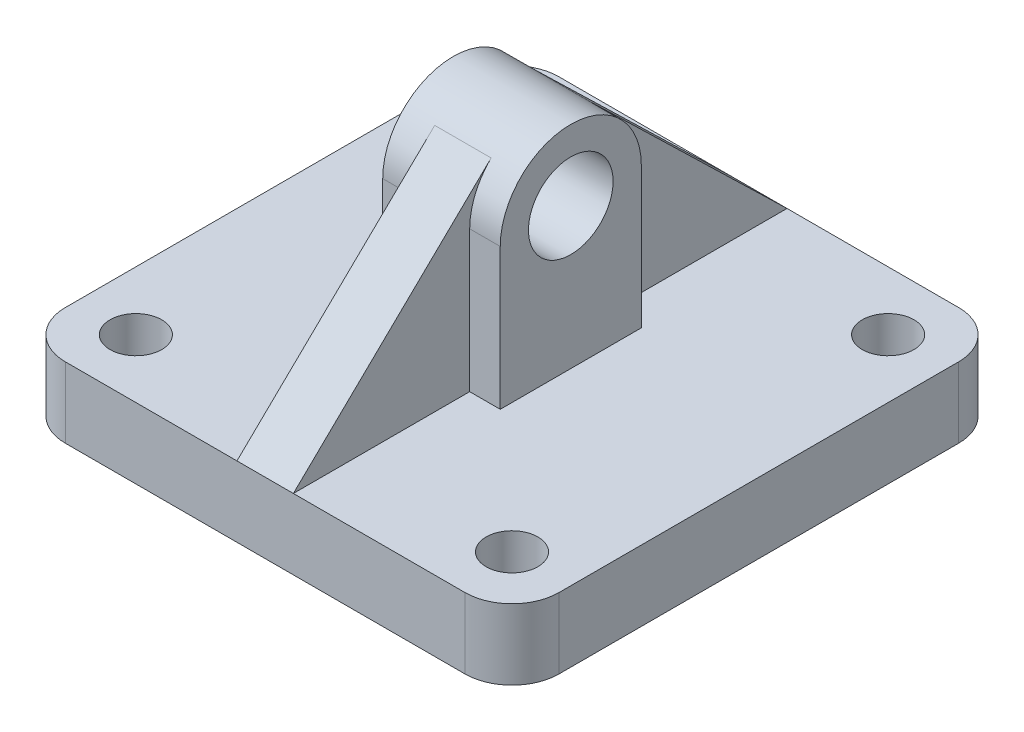
SolidWorks part; units mm, degrees
material "1060 Сплав"
ref_plane "Спереди" through (0, 0, 0) normal (0, 0, 1) x (1, 0, 0)
ref_plane "Сверху" through (0, 0, 0) normal (0, 1, 0) x (1, 0, 0)
ref_plane "Справа" through (0, 0, 0) normal (1, 0, 0) x (0, 0, -1)
sketch "Эскиз1" plane through (0, 0, 0) normal (0, 1, 0) x (1, 0, 0)
  line L1 (42.5, -52.5) -> (-42.5, -52.5)
  line L2 (52.5, -42.5) -> (52.5, 42.5)
  line L3 (42.5, 52.5) -> (-42.5, 52.5)
  line L4 (-52.5, -42.5) -> (-52.5, 42.5)
  line L5 (52.5, -52.5) -> (-52.5, 52.5) construction
  line L6 (52.5, 52.5) -> (-52.5, -52.5) construction
  arc A0 (-42.5, -52.5) -> (-52.5, -42.5) centre (-42.5, -42.5) cw
  arc A1 (42.5, -52.5) -> (52.5, -42.5) centre (42.5, -42.5) ccw
  arc A2 (52.5, 42.5) -> (42.5, 52.5) centre (42.5, 42.5) ccw
  arc A3 (-42.5, 52.5) -> (-52.5, 42.5) centre (-42.5, 42.5) ccw
  circle A4 centre (-40, -40) radius 5.5
  circle A5 centre (-40, 40) radius 5.5
  circle A6 centre (40, 40) radius 5.5
  circle A7 centre (40, -40) radius 5.5
  point P0 (0, 0)
  point P29 (0, 0)
  dimension "D2" = 10
  dimension "D3" = 11
  dimension "D1" = 105
  dimension "D4" = 40
  dimension "D5" = 4
extrude "Бобышка-Вытянуть1" add sketch "Эскиз1" along normal blind 15
sketch "Эскиз2" plane through (0, 0, 0) normal (0, -1, 0) x (1, 0, 0)
  circle A0 centre (0, 0) radius 35
  dimension "D1" = 70
extrude "Вырез-Вытянуть1" cut sketch "Эскиз2" against normal blind 10
sketch "Эскиз3" plane through (0, 0, -52.5) normal (0, 0, 1) x (1, 0, 0)
  line L0 (-42.5, 0) -> (42.5, 0) construction
  line L1 (0, -1000) -> (0, 49000) construction
  circle A0 centre (0, -5) radius 10
  point P2 (0, 0)
  dimension "D1" = 20
  dimension "D2" = 5
extrude "Вырез-Вытянуть2" cut sketch "Эскиз3" against normal up to surface (18.959 mm away)
sketch "Эскиз5" plane through (0, 0, 0) normal (1, 0, 0) x (0, 0, -1)
  line L0 (0, -1000) -> (0, 49000) construction
  line L1 (42.5, 0) -> (-42.5, 0) construction
  line L4 (15, 45) -> (15, 15)
  line L5 (15, 15) -> (-15, 15)
  line L6 (-15, 45) -> (-15, 15)
  arc A0 (15, 45) -> (-15, 45) centre (0, 45) ccw
  circle A1 centre (0, 45) radius 9
  dimension "D2" = 30
  dimension "D3" = 18
  dimension "D1" = 45
  dimension "D4" = 15
  dimension "D5" = 30
extrude "Бобышка-Вытянуть2" add sketch "Эскиз5" along normal mid plane 25
sketch "Эскиз7" plane through (0, 0, 0) normal (1, 0, 0) x (0, 0, -1)
  line L0 (52.5, 15) -> (10.4402, 55.7704)
  line L1 (-52.5, 15) -> (-10.4402, 55.7704)
  line L2 (10.4402, 55.7704) -> (10.4402, 15)
  line L3 (42.5, 15) -> (-42.5, 15) construction
  line L4 (10.4402, 15) -> (52.5, 15)
  line L5 (-10.4402, 55.7704) -> (-10.4402, 15)
  line L6 (-10.4402, 15) -> (-52.5, 15)
  arc A0 (15, 45) -> (-15, 45) centre (0, 45) ccw construction
extrude "Бобышка-Вытянуть3" add sketch "Эскиз7" along normal mid plane 12
